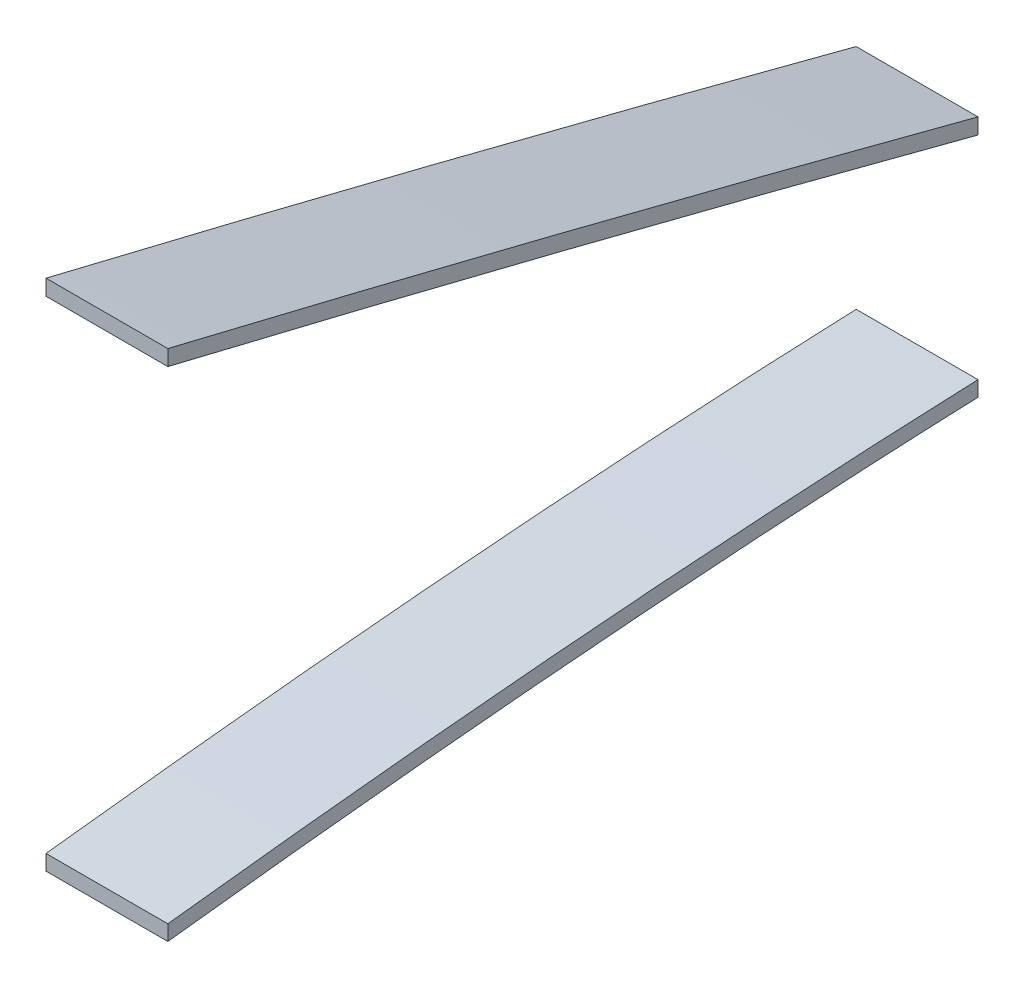
SolidWorks part; units mm, degrees
material "Balsa"
ref_plane "Front" through (0, 0, 0) normal (0, 0, 1) x (1, 0, 0)
ref_plane "Top" through (0, 0, 0) normal (0, 1, 0) x (1, 0, 0)
ref_plane "Right" through (0, 0, 0) normal (1, 0, 0) x (0, 0, -1)
sketch "Sketch1" plane through (0, 0, 0) normal (1, 0, 0) x (0, 0, -1)
  line L0 (616.0961, 23.2667) -> (616.0961, 10.5667) construction
  line L1 (616.0961, 24.8993) -> (616.0961, -28.6308)
  line L2 (700.5511, 3.5862) -> (700.5511, -21.7251)
  spline S0 degree 3 poles (304.4894, -1963.048) (904.56, -11.0089) (840.5576, -43.532) (789.3572, -23.4586) (777.0615, -18.6436) (760.5817, -13.0401) (739.9968, -7.1233) (715.5772, -0.3798) (687.647, 7.013) (656.6835, 14.9584) (623.1589, 23.2583) (587.5492, 31.6944) (550.3192, 40.0262) (511.9148, 48.0016) (472.7617, 55.3745) (433.2622, 61.9128) (393.7959, 67.4048) (354.7199, 71.6552) (316.357, 74.5357) (278.9313, 75.7536) (242.6994, 75.3938) (207.8706, 73.5467) (174.7468, 70.259) (143.6014, 65.7682) (114.7621, 60.1875) (88.5345, 53.6285) (65.199, 46.2382) (45.0006, 38.1339) (28.1586, 29.5092) (14.871, 20.5578) (6.1442, 12.3133) (1.9481, 6.1765) (0.6391, 3.0841) (0.217, 1.668) (-2.2377, -10.856) (31.8726, -26.5577) (-1993.0578, 155.2139) knots -0.166991 -0.166991 -0.166991 -0.166991 0.003802 0.014472 0.030564 0.051299 0.077028 0.107574 0.142399 0.180921 0.222525 0.266591 0.312515 0.35971 0.407632 0.455773 0.503669 0.550901 0.597096 0.641976 0.685512 0.727353 0.767354 0.805169 0.840471 0.872937 0.902335 0.928425 0.951113 0.970253 0.985871 0.993982 0.996753 0.997907 0.999293 1.04244 1.04244 1.04244 1.04244 only from (802.1511, -28.0117) to (0, 0) construction
  spline S1 degree 3 poles (802.1511, -28.0117) (801.1372, -27.7105) (797.2784, -26.5642) (789.3572, -23.4586) (777.0615, -18.6436) (760.5817, -13.0401) (739.9968, -7.1233) (715.5772, -0.3798) (687.647, 7.013) (656.6835, 14.9584) (623.1589, 23.2583) (587.5492, 31.6944) (550.3192, 40.0262) (511.9148, 48.0016) (472.7617, 55.3745) (433.2622, 61.9128) (393.7959, 67.4048) (354.7199, 71.6552) (316.357, 74.5357) (278.9313, 75.7536) (242.6994, 75.3938) (207.8706, 73.5467) (174.7468, 70.259) (143.6014, 65.7682) (114.7621, 60.1875) (88.5345, 53.6285) (65.199, 46.2382) (45.0006, 38.1339) (28.1586, 29.5092) (14.871, 20.5578) (6.1442, 12.3133) (1.9481, 6.1765) (0.6391, 3.0841) (0.217, 1.668) (0.0426, 0.7778) (0.0107, 0.1963) (0, 0) knots 0 0 0 0 0.003802 0.014472 0.030564 0.051299 0.077028 0.107574 0.142399 0.180921 0.222525 0.266591 0.312515 0.35971 0.407632 0.455773 0.503669 0.550901 0.597096 0.641976 0.685512 0.727353 0.767354 0.805169 0.840471 0.872937 0.902335 0.928425 0.951113 0.970253 0.985871 0.993982 0.996753 0.997907 0.999293 1 1 1 1
  spline S2 degree 3 poles (-1994.7901, -130.8385) (49.5083, 45.0487) (-3.9103, 18.1854) (0.5702, -4.3968) (2.5361, -10.6164) (7.9982, -20.5501) (16.1137, -34.185) (25.7513, -48.9002) (36.932, -62.9388) (49.3364, -75.9186) (65.2269, -85.625) (84.4528, -91.7174) (106.8521, -96.1515) (132.5109, -98.5722) (161.1944, -99.0924) (192.7613, -97.7042) (227.0382, -94.5118) (263.8348, -89.6638) (302.9215, -83.3884) (344.0178, -75.9778) (386.7768, -67.7807) (430.7746, -59.2023) (475.4963, -50.6638) (520.3353, -42.6036) (564.5889, -35.4228) (607.4709, -29.4733) (648.1275, -25.0145) (685.6676, -22.1862) (719.1968, -21.0048) (747.8303, -21.2786) (770.6884, -22.8547) (787.0914, -25.0735) (855.7552, -37.3672) (910.4178, -89.1553) (1388.6423, 1880.9845) knots -0.071347 -0.071347 -0.071347 -0.071347 0.001821 0.004613 0.009135 0.024676 0.044153 0.064937 0.086321 0.107138 0.1276 0.150893 0.177565 0.207668 0.241222 0.278203 0.318526 0.362031 0.408465 0.457479 0.508614 0.561296 0.614835 0.668438 0.721214 0.772202 0.820393 0.864766 0.904324 0.938132 0.965242 0.98469 0.99621 1.210002 1.210002 1.210002 1.210002 only from (0, 0) to (802.1511, -28.0117) construction
  spline S3 degree 3 poles (0, 0) (0.0175, -0.519) (0.0617, -1.8338) (0.5702, -4.3968) (2.5361, -10.6164) (7.9982, -20.5501) (16.1137, -34.185) (25.7513, -48.9002) (36.932, -62.9388) (49.3364, -75.9186) (65.2269, -85.625) (84.4528, -91.7174) (106.8521, -96.1515) (132.5109, -98.5722) (161.1944, -99.0924) (192.7613, -97.7042) (227.0382, -94.5118) (263.8348, -89.6638) (302.9215, -83.3884) (344.0178, -75.9778) (386.7768, -67.7807) (430.7746, -59.2023) (475.4963, -50.6638) (520.3353, -42.6036) (564.5889, -35.4228) (607.4709, -29.4733) (648.1275, -25.0145) (685.6676, -22.1862) (719.1968, -21.0048) (747.8303, -21.2786) (770.6884, -22.8547) (787.0914, -25.0735) (796.8423, -26.8193) (801.0977, -27.7751) (802.1511, -28.0117) knots 0 0 0 0 0.001821 0.004613 0.009135 0.024676 0.044153 0.064937 0.086321 0.107138 0.1276 0.150893 0.177565 0.207668 0.241222 0.278203 0.318526 0.362031 0.408465 0.457479 0.508614 0.561296 0.614835 0.668438 0.721214 0.772202 0.820393 0.864766 0.904324 0.938132 0.965242 0.98469 0.99621 1 1 1 1
  spline S4 degree 1 poles (784.1065, -23.1184) (1.589, -0.0169) knots 0 0 1 1 construction
  spline S5 degree 1 poles (1.589, -0.0169) (784.1065, -23.1184) knots 0 0 1 1 construction
  spline S6 degree 3 poles (784.1065, -23.1184) (780.1603, -21.5942) (772.229, -18.642) (760.1745, -14.6722) (747.9911, -11.0613) (731.6457, -6.456) (711.1768, -0.8453) (678.3297, 7.8115) (637.1713, 18.2575) (587.6183, 30.1162) (537.8777, 41.1375) (487.9189, 51.0912) (437.7208, 59.724) (387.2787, 66.7289) (345.0506, 70.936) (311.1879, 73.0641) (277.2796, 74.2092) (243.3427, 73.88) (209.4764, 71.9586) (184.1438, 69.6475) (158.905, 66.4678) (133.8072, 62.3586) (108.9155, 57.1874) (88.425, 51.8354) (72.2738, 46.7811) (60.3184, 42.5401) (48.5771, 37.7737) (37.1197, 32.3878) (27.9272, 27.2538) (20.9064, 22.6554) (15.8717, 18.9075) (11.1186, 14.8241) (7.5582, 11.0807) (5.0251, 7.8349) (3.3892, 5.2955) (2.3111, 3.0614) (1.8056, 1.4859) (1.654, 0.7258) (1.6104, 0.3499) (1.5955, 0.1003) (1.589, -0.0169) knots 0.0223 0.0223 0.0223 0.0223 0.037575 0.05285 0.068125 0.083401 0.113951 0.144502 0.205603 0.266703 0.327804 0.388905 0.450006 0.511107 0.572208 0.602759 0.633309 0.69441 0.724961 0.755511 0.786062 0.816612 0.847162 0.877713 0.892988 0.908263 0.923539 0.938814 0.954089 0.961727 0.969364 0.977002 0.98464 0.988458 0.992277 0.996096 0.998005 0.99896 0.999438 0.999915 0.999915 0.999915 0.999915
  spline S7 degree 3 poles (1.589, -0.0169) (1.5978, -0.2781) (1.617, -0.8171) (1.6706, -1.5251) (1.7727, -2.2395) (1.9645, -3.217) (2.2822, -4.4731) (2.892, -6.4557) (3.825, -8.9127) (5.5748, -12.7649) (8.1549, -17.4947) (12.5101, -25.0363) (18.1123, -34.2943) (25.2301, -45.181) (31.6891, -53.8227) (37.2128, -60.4726) (42.9501, -66.9629) (50.6018, -74.4394) (61.3489, -81.5128) (73.1594, -86.5673) (85.641, -90.1112) (98.3223, -92.8576) (115.4237, -95.4885) (137.057, -97.1574) (163.0971, -97.3914) (189.1354, -96.2564) (215.1195, -94.0861) (241.0338, -91.1098) (275.4921, -86.3076) (318.4041, -79.1225) (369.7356, -69.4844) (421.0135, -59.4768) (472.335, -49.6151) (523.7845, -40.3589) (575.4257, -32.1357) (627.3021, -25.4119) (670.7418, -21.5032) (705.604, -19.8163) (731.789, -19.4122) (758.0003, -20.1502) (775.4469, -21.8673) (784.1065, -23.1184) knots 0.000082 0.000082 0.000082 0.000082 0.001038 0.001993 0.002948 0.003903 0.005814 0.007724 0.011545 0.015366 0.023009 0.030651 0.045935 0.061219 0.076503 0.084145 0.091787 0.107071 0.122355 0.137639 0.152923 0.168208 0.183492 0.21406 0.244628 0.275196 0.305765 0.336333 0.366901 0.428038 0.489174 0.55031 0.611447 0.672583 0.73372 0.794856 0.855993 0.886561 0.917129 0.947697 0.978266 0.978266 0.978266 0.978266
  dimension "D2" = 101.6
  dimension "D1" = 1.5875
extrude "Boss-Extrude1" add sketch "Sketch1" along normal mid plane 12.7 contours S6 L2 S1 L1 | S7 L1 S3 L2
